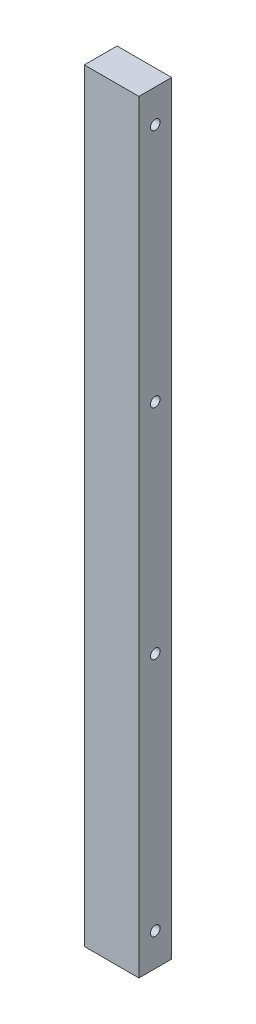
SolidWorks part; units mm, degrees
ref_plane "Front Plane" through (0, 0, 0) normal (0, 0, 1) x (1, 0, 0)
ref_plane "Top Plane" through (0, 0, 0) normal (0, 1, 0) x (1, 0, 0)
ref_plane "Right Plane" through (0, 0, 0) normal (1, 0, 0) x (0, 0, -1)
sketch "草图1" plane through (0, 0, 0) normal (0, 0, 1) x (1, 0, 0)
  line L0 (-50, 760) -> (-50, -90) construction
  line L1 (0, 700) -> (-50, 700)
  line L2 (0, 700) -> (0, 0)
  line L3 (0, 0) -> (-50, 0)
  line L4 (-50, 700) -> (-50, 0)
  dimension "D1" = 50
extrude "凸台-拉伸1" add sketch "草图1" against normal blind 30
hole_wizard "M10x1.25 螺纹孔1" positions "草图3" profile "草图2" tap size "M10x1.25" standard "Ansi Metric"
sketch "草图3" plane through (0, 0, 0) normal (1, 0, 0) x (0, 0, -1)
  line L0 (30, 0) -> (0, 0) construction
  line L1 (30, 0) -> (30, 700) construction
  line L2 (30, 700) -> (0, 700) construction
  point P0 (15, 670)
  point P3 (15, 450)
  point P6 (15, 250)
  point P9 (15, 30)
  dimension "D1" = 30
  dimension "D2" = 250
  dimension "D3" = 15
  dimension "D4" = 15
  dimension "D5" = 30
  dimension "D6" = 250
  dimension "D7" = 15
  dimension "D8" = 15
sketch "草图2" plane through (0, 670, -15) normal (0, 1, 0) x (0, 0, -1)
  line L0 (0, 0) -> (0, 26.3938)
  line L1 (0, 26.3938) -> (4.4, 23.75)
  line L2 (4.4, 23.75) -> (4.4, 0)
  line L5 (4.4, 0) -> (0, 0)
  line L10 (0, 26.3938) -> (-4.4, 23.75) construction
  line L11 (0, -6.35) -> (0, 107.95) construction
  dimension "螺纹孔钻头直径" = 8.8
  dimension "螺纹孔钻头深度" = 23.75
  dimension "导头角度" = 118
cosmetic thread "孔螺蚊线1" parameters "D1"=20, "D2"=10
cosmetic thread "孔螺蚊线2" parameters "D1"=20, "D2"=10
cosmetic thread "孔螺蚊线3" parameters "D1"=20, "D2"=10
cosmetic thread "孔螺蚊线4" parameters "D1"=20, "D2"=10
hole_wizard "M12x1.5 螺纹孔1" positions "草图5" profile "草图4" tap size "M12x1.5" standard "Ansi Metric"
sketch "草图5" plane through (-50, 0, 0) normal (-1, 0, 0) x (0, 0, 1)
  point P0 (-15, 535)
  point P3 (-15, 135)
sketch "草图4" plane through (-50, 535, -15) normal (0, 1, 0) x (0, 0, 1)
  line L0 (0, 0) -> (0, 31.6545)
  line L1 (0, 31.6545) -> (5.25, 28.5)
  line L2 (5.25, 28.5) -> (5.25, 0)
  line L5 (5.25, 0) -> (0, 0)
  line L10 (0, 31.6545) -> (-5.25, 28.5) construction
  line L11 (0, -6.35) -> (0, 107.95) construction
  dimension "螺纹孔钻头直径" = 10.5
  dimension "螺纹孔钻头深度" = 28.5
  dimension "导头角度" = 118
cosmetic thread "孔螺蚊线5" parameters "D1"=24, "D2"=12
cosmetic thread "孔螺蚊线6" parameters "D1"=24, "D2"=12
